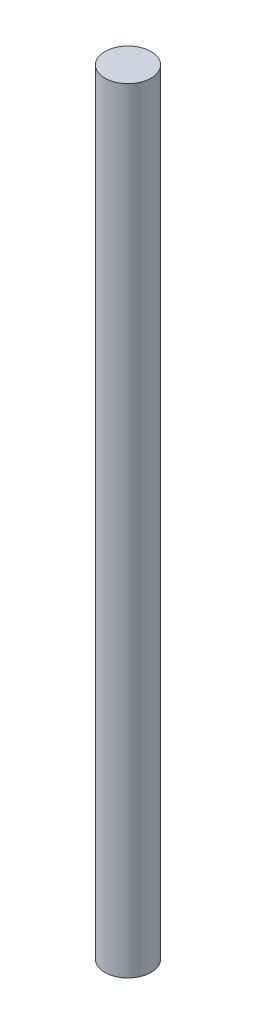
SolidWorks part; units mm, degrees
ref_plane "Front" through (0, 0, 0) normal (0, 0, 1) x (1, 0, 0)
ref_plane "Top" through (0, 0, 0) normal (0, 1, 0) x (1, 0, 0)
ref_plane "Right" through (0, 0, 0) normal (1, 0, 0) x (0, 0, -1)
sketch "Sketch1" plane through (0, 0, 0) normal (0, 1, 0) x (1, 0, 0)
  circle A0 centre (0, 0) radius 8.89
extrude "Boss-Extrude1" add sketch "Sketch1" along normal blind 298.45
